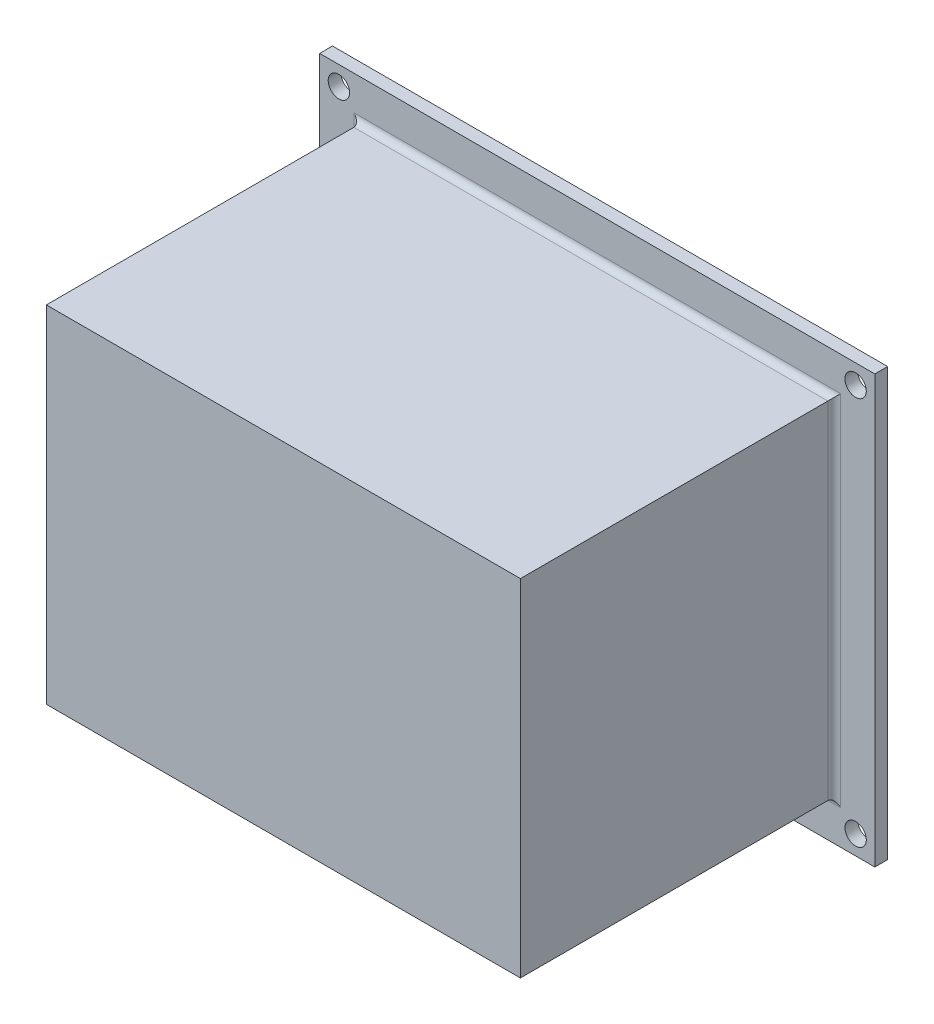
SolidWorks part; units mm, degrees
ref_plane "前视基准面" through (0, 0, 0) normal (0, 0, 1) x (1, 0, 0)
ref_plane "上视基准面" through (0, 0, 0) normal (0, 1, 0) x (1, 0, 0)
ref_plane "右视基准面" through (0, 0, 0) normal (1, 0, 0) x (0, 0, -1)
sketch "草图1" plane through (0, 0, 0) normal (0, 0, 1) x (1, 0, 0)
  line L1 (-65, 50) -> (65, 50)
  line L2 (-65, 50) -> (-65, -50)
  line L3 (-65, -50) -> (65, -50)
  line L4 (65, 50) -> (65, -50)
  line L5 (0, -50) -> (0, 50) construction
  line L6 (-65, 0) -> (65, 0) construction
  line L7 (-52.5, 37.5) -> (52.5, 37.5)
  line L8 (-52.5, 37.5) -> (-52.5, -37.5)
  line L9 (-52.5, -37.5) -> (52.5, -37.5)
  line L10 (52.5, 37.5) -> (52.5, -37.5)
  line L11 (0, -37.5) -> (0, 37.5) construction
  line L12 (-52.5, 0) -> (52.5, 0) construction
  point P0 (0, 0)
  point P4 (0, 0)
  dimension "D1" = 105
  dimension "D2" = 130
  dimension "D3" = 75
  dimension "D4" = 100
extrude "凸台-拉伸1" add sketch "草图1" along normal blind 3
sketch "草图2" plane through (0, 0, 3) normal (0, 0, 1) x (1, 0, 0)
  line L1 (-55.5, 40.5) -> (55.5, 40.5)
  line L2 (-55.5, 40.5) -> (-55.5, -40.5)
  line L3 (-55.5, -40.5) -> (55.5, -40.5)
  line L4 (55.5, 40.5) -> (55.5, -40.5)
  line L5 (0, -40.5) -> (0, 40.5) construction
  line L6 (-55.5, 0) -> (55.5, 0) construction
  line L9 (-52.5, 37.5) -> (52.5, 37.5)
  line L10 (-52.5, 37.5) -> (-52.5, -37.5)
  line L11 (-52.5, -37.5) -> (52.5, -37.5)
  line L12 (52.5, 37.5) -> (52.5, -37.5)
  line L13 (0, -37.5) -> (0, 37.5) construction
  line L14 (-52.5, 0) -> (52.5, 0) construction
  point P0 (0, 0)
  point P8 (0, 0)
  dimension "D1" = 3
  dimension "D2" = 3
extrude "凸台-拉伸2" add sketch "草图2" along normal blind 73.5
fillet "圆角1" radius 1.5 4 edges at (0, -40.5, 3) (-55.5, 0, 3) (0, 40.5, 3) (55.5, 0, 3)
sketch "草图4" plane through (0, 0, 3) normal (0, 0, 1) x (1, 0, 0)
  line L0 (0, 0) -> (0, 18.6703) construction
  line L1 (0, 0) -> (18.252, 0) construction
  line L2 (65, 50) -> (-65, 50) construction
  line L3 (-65, 50) -> (-65, -50) construction
  circle A0 centre (-60.5, 45.5) radius 2.5
  circle A1 centre (60.5, 45.5) radius 2.5
  circle A2 centre (60.5, -45.5) radius 2.5
  circle A3 centre (-60.5, -45.5) radius 2.5
  dimension "D1" = 5
  dimension "D2" = 4.5
  dimension "D3" = 4.5
extrude "切除-拉伸2" cut sketch "草图4" against normal blind 113.5
sketch "草图6" plane through (-55.5, 0, 0) normal (-1, 0, 0) x (0, 0, 1)
  line L1 (25, 0) -> (47.5, -12.9904)
  line L2 (47.5, -12.9904) -> (47.5, 12.9904)
  line L3 (47.5, 12.9904) -> (25, 0)
  circle A0 centre (40, 0) radius 7.5 construction
  dimension "D1" = 15
  dimension "D2" = 40
extrude "切除-拉伸4" cut sketch "草图6" against normal blind 73.5
sketch "草图7" plane through (0, 0, 76.5) normal (0, 0, 1) x (1, 0, 0)
  line L1 (-52.5, -37.5) -> (52.5, -37.5)
  line L2 (-52.5, -37.5) -> (-52.5, 37.5)
  line L3 (-52.5, 37.5) -> (52.5, 37.5)
  line L4 (52.5, -37.5) -> (52.5, 37.5)
  line L5 (0, 37.5) -> (0, -37.5) construction
  line L6 (-52.5, 0) -> (52.5, 0) construction
  point P0 (0, 0)
extrude "凸台-拉伸3" add sketch "草图7" against normal blind 2.5
